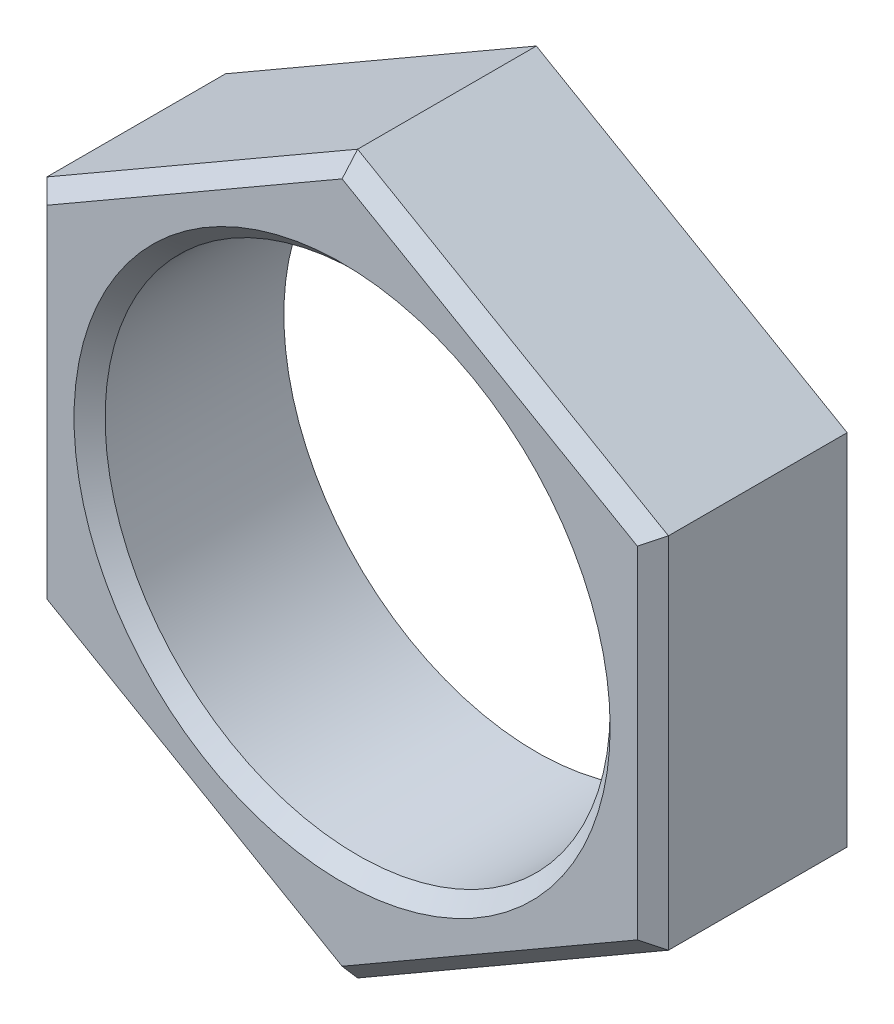
SolidWorks part; units mm, degrees
material "AISI 1015 Steel, Cold Drawn (SS)"
ref_plane "Front Plane" through (0, 0, 0) normal (0, 0, 1) x (1, 0, 0)
ref_plane "Top Plane" through (0, 0, 0) normal (0, 1, 0) x (1, 0, 0)
ref_plane "Right Plane" through (0, 0, 0) normal (1, 0, 0) x (0, 0, -1)
sketch "Sketch1" plane through (0, 0, 0) normal (0, 0, 1) x (1, 0, 0)
  line L1 (0, 29.3294) -> (-25.4, 14.6647)
  line L2 (-25.4, 14.6647) -> (-25.4, -14.6647)
  line L3 (-25.4, -14.6647) -> (0, -29.3294)
  line L4 (0, -29.3294) -> (25.4, -14.6647)
  line L5 (25.4, -14.6647) -> (25.4, 14.6647)
  line L6 (25.4, 14.6647) -> (0, 29.3294)
  circle A0 centre (0, 0) radius 20.6375
  circle A1 centre (0, 0) radius 25.4 construction
  dimension "D1" = 41.275
  dimension "D2" = 50.8
extrude "Boss-Extrude1" add sketch "Sketch1" along normal blind 15.875
chamfer "Chamfer1" distance 1.27 angle 45 7 edges at (20.6375, 0, 15.875) (25.4, 0, 15.875) (12.7, -21.997, 15.875) (-12.7, -21.997, 15.875) (-25.4, 0, 15.875) (-12.7, 21.997, 15.875) (12.7, 21.997, 15.875)
